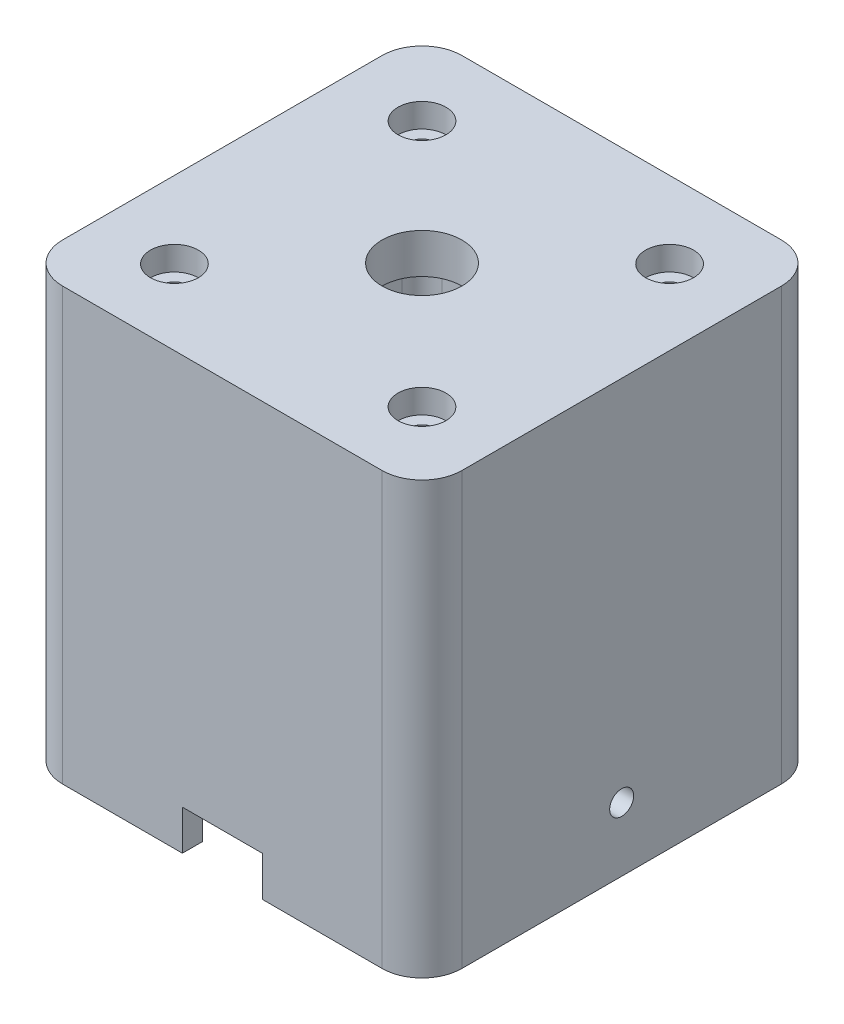
SolidWorks part; units mm, degrees
ref_plane "Front Plane" through (0, 0, 0) normal (0, 0, 1) x (1, 0, 0)
ref_plane "Top Plane" through (0, 0, 0) normal (0, 1, 0) x (1, 0, 0)
ref_plane "Right Plane" through (0, 0, 0) normal (1, 0, 0) x (0, 0, -1)
sketch "Sketch1" plane through (0, 0, 0) normal (0, 1, 0) x (1, 0, 0)
  line L1 (-22.5, 22.5) -> (22.5, 22.5)
  line L2 (-22.5, 22.5) -> (-22.5, -22.5)
  line L3 (-22.5, -22.5) -> (22.5, -22.5)
  line L4 (22.5, 22.5) -> (22.5, -22.5)
  line L5 (-22.5, 22.5) -> (22.5, -22.5) construction
  line L6 (-22.5, -22.5) -> (22.5, 22.5) construction
  line L7 (-25, 25) -> (25, 25)
  line L8 (-25, 25) -> (-25, -25)
  line L9 (-25, -25) -> (25, -25)
  line L10 (25, 25) -> (25, -25)
  line L11 (-25, 25) -> (25, -25) construction
  line L12 (-25, -25) -> (25, 25) construction
  point P0 (0, 0)
  point P6 (0, 0)
  dimension "D1" = 45
  dimension "D2" = 50
extrude "Boss-Extrude1" add sketch "Sketch1" along normal blind 47
sketch "Sketch3" plane through (0, 47, 0) normal (0, 1, 0) x (1, 0, 0)
  line L1 (-25, 25) -> (25, 25)
  line L2 (-25, 25) -> (-25, -25)
  line L3 (-25, -25) -> (25, -25)
  line L4 (25, 25) -> (25, -25)
  line L5 (-25, 25) -> (25, -25) construction
  line L6 (-25, -25) -> (25, 25) construction
  point P0 (0, 0)
extrude "Boss-Extrude3" add sketch "Sketch3" along normal blind 7
sketch "Sketch5" plane through (0, 47, 0) normal (0, -1, 0) x (1, 0, 0)
  circle A0 centre (0, 0) radius 11.5
  dimension "D1" = 23
extrude "Cut-Extrude1" cut sketch "Sketch5" against normal blind 2
sketch "Sketch6" plane through (0, 49, 0) normal (0, -1, 0) x (1, 0, 0)
  circle A0 centre (0, 0) radius 5
  dimension "D1" = 10
extrude "Cut-Extrude2" cut sketch "Sketch6" against normal through all
sketch "Sketch7" plane through (0, 54, 0) normal (0, 1, 0) x (1, 0, 0)
  line L0 (-25, 15.4) -> (25, 15.4) construction
  line L1 (-25, 25) -> (-25, -25) construction
  line L2 (25, -25) -> (25, 25) construction
  line L4 (25, 25) -> (-25, 25) construction
  line L5 (-15.4, 25) -> (-15.4, -25) construction
  line L6 (-25, -25) -> (25, -25) construction
  circle A0 centre (-15.4, 15.4) radius 2.5
  circle A1 centre (15.6, 15.4) radius 2.5
  circle A2 centre (15.6, -15.6) radius 2.5
  circle A3 centre (-15.4, -15.6) radius 2.5
  dimension "D1" = 5
  dimension "D2" = 9.6
  dimension "D3" = 9.6
  dimension "D4" = 2
  dimension "D5" = 2
fillet "Fillet2" radius 5 1 edges at (25, 27, 25)
fillet "Fillet3" radius 5 1 edges at (25, 27, -25)
fillet "Fillet4" radius 5 1 edges at (-25, 27, -25)
fillet "Fillet5" radius 5 1 edges at (-25, 27, 25)
fillet "Fillet7" radius 2.5 1 edges at (-22.5, 23.5, 22.5)
fillet "Fillet8" radius 2.5 1 edges at (22.5, 23.5, 22.5)
fillet "Fillet9" radius 2.5 1 edges at (22.5, 23.5, -22.5)
fillet "Fillet10" radius 2.5 1 edges at (-22.5, 23.5, -22.5)
sketch "Sketch9" plane through (0, 0, 25) normal (0, 0, 1) x (1, 0, 0)
  line L0 (0, -27.5) -> (0, 27.5) construction
  line L1 (-5, 5) -> (5, 5)
  line L2 (-5, 5) -> (-5, 0)
  line L3 (-5, 0) -> (5, 0)
  line L4 (5, 5) -> (5, 0)
  line L5 (-5, 5) -> (5, 0) construction
  line L6 (-5, 0) -> (5, 5) construction
  line L7 (27.5, 0) -> (-27.5, 0) construction
  point P0 (0, 2.5)
  dimension "D1" = 10
  dimension "D2" = 5
extrude "Cut-Extrude5" cut sketch "Sketch9" against normal blind 13
sketch "Sketch10" plane through (25, 0, 0) normal (1, 0, 0) x (0, 0, -1)
  circle A0 centre (0, 8) radius 1.5
  point P0 (0, 8)
extrude "Cut-Extrude6" cut sketch "Sketch10" against normal blind 10
pattern_circular "CirPattern1" count 4 over 360 about axis through (0, 54, 0) along (0, -1, 0) skipping 1 of "Cut-Extrude6"
hole_wizard "Hole1" positions "3DSketch1" profile "Sketch13" legacy
sketch3d "3DSketch1"
  point P0 (-15.4, 54, -15.4)
  point P3 (15.6, 54, -15.4)
  point P6 (15.6, 54, 15.6)
  point P9 (-15.4, 54, 15.6)
sketch "Sketch13" plane through (-15.4, 54, -15.4) normal (1, 0, 0) x (0, 0, 1)
  line L0 (0, 0) -> (0, 12)
  line L1 (0, 12) -> (1.5, 12)
  line L2 (1.5, 12) -> (1.5, 3)
  line L3 (1.5, 3) -> (3, 3)
  line L4 (3, 3) -> (3, 0)
  line L5 (3, 0) -> (0, 0)
  line L6 (0, 110) -> (0, -10) construction
  dimension "Diameter" = 3
  dimension "Depth" = 12
  dimension "C-Bore Diameter" = 6
  dimension "C-Bore Depth" = 3
